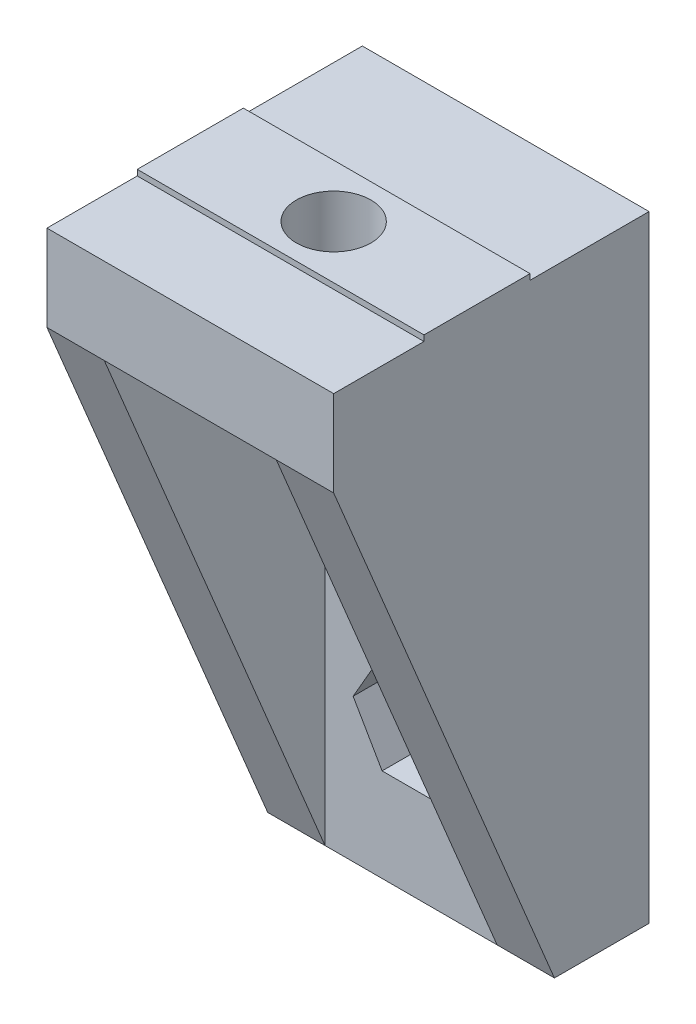
SolidWorks part; units mm, degrees
ref_plane "Спереди" through (0, 0, 0) normal (0, 0, 1) x (1, 0, 0)
ref_plane "Сверху" through (0, 0, 0) normal (0, 1, 0) x (1, 0, 0)
ref_plane "Справа" through (0, 0, 0) normal (1, 0, 0) x (0, 0, -1)
sketch "Эскиз3" plane through (0, 0, 0) normal (0, 0, 1) x (1, 0, 0)
  line L1 (10, 0) -> (10, 37)
  line L2 (10, 37) -> (-10, 37)
  line L3 (-10, 37) -> (-10, 0)
  line L4 (10, 0) -> (-10, 0)
  point P5 (0, 0)
  dimension "D2" = 37
  dimension "D1" = 20
extrude "Бобышка-Вытянуть2" add sketch "Эскиз3" along normal blind 6.6 separate body
sketch "Эскиз10" plane through (0, 0, 0) normal (0, 0, -1) x (-1, 0, 0)
  line L0 (-10, 0) -> (-10, 37) construction
  line L5 (10, 0) -> (-10, 0) construction
  circle A2 centre (0, 10) radius 2.2
  dimension "D3" = 4.4
  dimension "D6" = 10
  dimension "D9" = 10
extrude "Вырез-Вытянуть3" cut sketch "Эскиз10" against normal through all
sketch "Эскиз6" plane through (0, 0, 6.6) normal (0, 0, 1) x (1, 0, 0)
  line L1 (4.0415, 10) -> (2.0207, 13.5)
  line L2 (2.0207, 13.5) -> (-2.0207, 13.5)
  line L3 (-2.0207, 13.5) -> (-4.0415, 10)
  line L4 (-4.0415, 10) -> (-2.0207, 6.5)
  line L5 (-2.0207, 6.5) -> (2.0207, 6.5)
  line L6 (2.0207, 6.5) -> (4.0415, 10)
  circle A0 centre (0, 10) radius 3.5 construction
  circle A3 centre (0, 10) radius 2.2 construction
  dimension "D2" = 7
extrude "Вырез-Вытянуть2" cut sketch "Эскиз6" against normal blind 3.4
sketch "Эскиз11" plane through (0, 37, 0) normal (0, 1, 0) x (1, 0, 0)
  line L1 (-10, 0) -> (10, 0)
  line L2 (-10, 0) -> (-10, -22)
  line L3 (-10, -22) -> (10, -22)
  line L4 (10, 0) -> (10, -22)
  dimension "D1" = 22
extrude "Бобышка-Вытянуть5" add sketch "Эскиз11" along normal blind 6
sketch "Эскиз9" plane through (0, 43, -43.4) normal (0, -1, 0) x (1, 0, 0)
  line L0 (-10, 65.4) -> (10, 65.4) construction
  line L1 (-10, 59.1) -> (10, 59.1)
  line L2 (-10, 59.1) -> (-10, 51.7)
  line L3 (-10, 51.7) -> (10, 51.7)
  line L4 (10, 59.1) -> (10, 51.7)
  line L7 (-10, 43.4) -> (-10, 65.4) construction
  line L8 (10, 65.4) -> (10, 43.4) construction
  point P10 (-10, 55.4)
  dimension "D1" = 7.4
  dimension "D2" = 10
extrude "Бобышка-Вытянуть4" add sketch "Эскиз9" against normal blind 0.4
sketch "Эскиз13" plane through (0, 43.4, 0) normal (0, 1, 0) x (1, 0, 0)
  line L0 (-10, -15.7) -> (-10, -22) construction
  line L1 (-10, -22) -> (10, -22) construction
  circle A0 centre (0, -12) radius 2.6
  dimension "D1" = 5.2
  dimension "D3" = 10
  dimension "D2" = 10
extrude "Вырез-Вытянуть4" cut sketch "Эскиз13" against normal through all
sketch "Эскиз17" plane through (-10, 0, 0) normal (-1, 0, 0) x (0, 0, 1)
  line L0 (22, 37) -> (6.6, 37)
  line L1 (6.6, 37) -> (6.6, 0)
  line L2 (6.6, 0) -> (22, 37)
extrude "Бобышка-Вытянуть6" add sketch "Эскиз17" against normal blind 4
mirror "Зеркальное отражение1" about plane through (0, 0, 0) normal (1, 0, 0) of "Бобышка-Вытянуть6"
